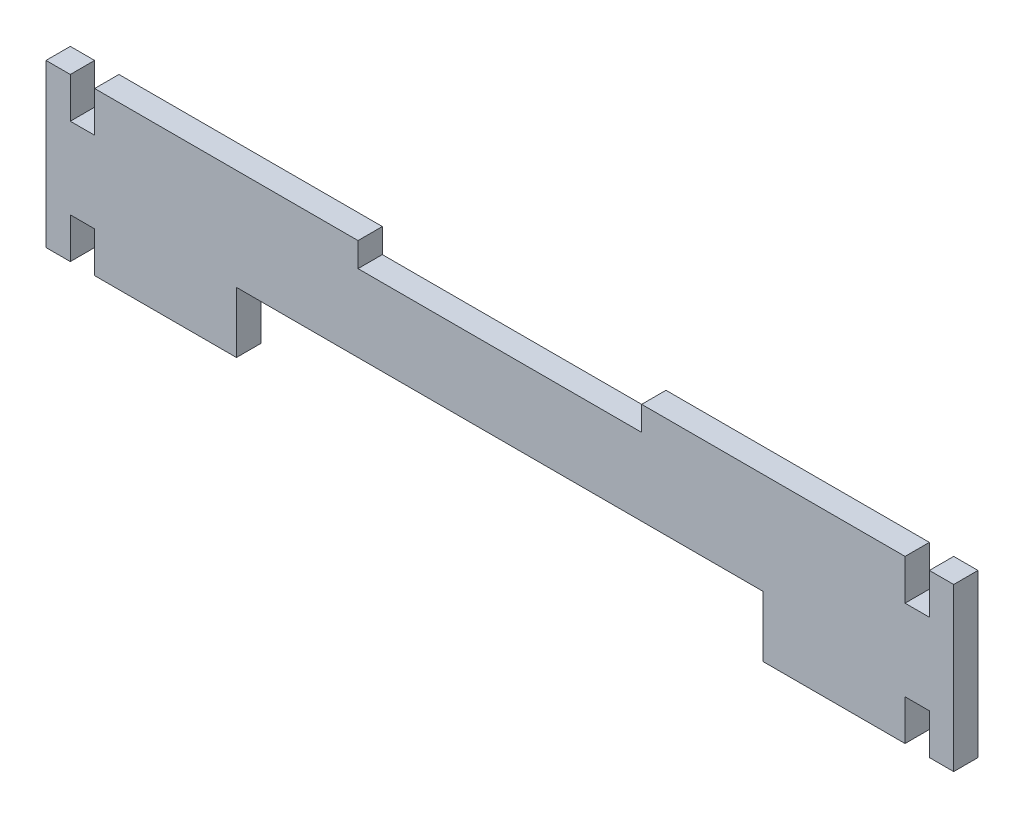
SolidWorks part; units mm, degrees
ref_plane "Front" through (0, 0, 0) normal (0, 0, 1) x (1, 0, 0)
ref_plane "Top" through (0, 0, 0) normal (0, 1, 0) x (1, 0, 0)
ref_plane "Right" through (0, 0, 0) normal (1, 0, 0) x (0, 0, -1)
sketch "Sketch1" plane through (0, 0, 0) normal (0, 0, 1) x (1, 0, 0)
  line L1 (0, 0) -> (-224, 0)
  line L2 (0, 0) -> (0, 40)
  line L3 (0, 40) -> (-224, 40)
  line L4 (-224, 0) -> (-224, 40)
  dimension "D1" = 40
  dimension "D2" = 224
extrude "Boss-Extrude1" add sketch "Sketch1" along normal blind 6
sketch "Sketch2" plane through (0, 0, 6) normal (0, 0, 1) x (1, 0, 0)
  line L0 (0, 40) -> (-224, 40) construction
  line L1 (-218, 40) -> (-212, 40)
  line L2 (-218, 40) -> (-218, 30)
  line L3 (-218, 30) -> (-212, 30)
  line L4 (-212, 40) -> (-212, 30)
  line L5 (-224, 40) -> (-224, 0) construction
  dimension "D1" = 10
  dimension "D2" = 6
  dimension "D3" = 6
extrude "Cut-Extrude1" cut sketch "Sketch2" against normal through all
pattern_linear "LPattern1" count 2 spacing 206 along (1, 0, 0) count 2 spacing 30 along (0, -1, 0) of "Cut-Extrude1"
sketch "Sketch3" plane through (0, 0, 6) normal (0, 0, 1) x (1, 0, 0)
  line L0 (-12, 40) -> (-212, 40) construction
  line L1 (-147, 40) -> (-77, 40)
  line L2 (-147, 40) -> (-147, 34)
  line L3 (-147, 34) -> (-77, 34)
  line L4 (-77, 40) -> (-77, 34)
  point P6 (-112, 40)
  point P7 (-112, 40)
  dimension "D1" = 70
  dimension "D2" = 6
extrude "Cut-Extrude2" cut sketch "Sketch3" against normal through all
sketch "Sketch4" plane through (0, 0, 6) normal (0, 0, 1) x (1, 0, 0)
  line L0 (-212, 0) -> (-12, 0) construction
  line L1 (-177, 0) -> (-47, 0)
  line L2 (-177, 0) -> (-177, 15)
  line L3 (-177, 15) -> (-47, 15)
  line L4 (-47, 0) -> (-47, 15)
  point P6 (-112, 0)
  point P7 (-112, 0)
  dimension "D1" = 15
  dimension "D2" = 130
extrude "Cut-Extrude3" cut sketch "Sketch4" against normal blind 10
